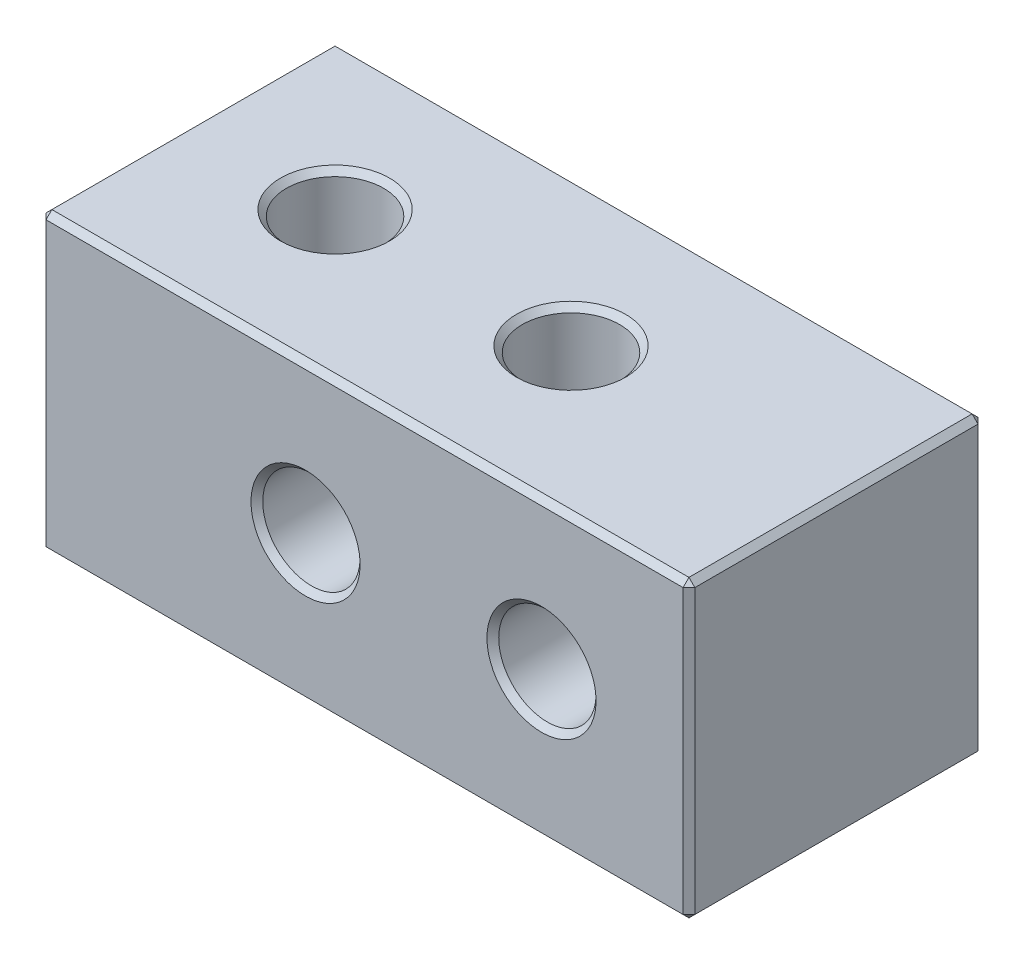
SolidWorks part; units mm, degrees
ref_plane "前视基准面" through (0, 0, 0) normal (0, 0, 1) x (1, 0, 0)
ref_plane "上视基准面" through (0, 0, 0) normal (0, 1, 0) x (1, 0, 0)
ref_plane "右视基准面" through (0, 0, 0) normal (1, 0, 0) x (0, 0, -1)
sketch "草图1" plane through (0, 0, 0) normal (0, 1, 0) x (1, 0, 0)
  line L1 (-11, 5) -> (11, 5)
  line L2 (-11, 5) -> (-11, -5)
  line L3 (-11, -5) -> (11, -5)
  line L4 (11, 5) -> (11, -5)
  line L5 (-11, 5) -> (11, -5) construction
  line L6 (-11, -5) -> (11, 5) construction
  point P0 (0, 0)
  dimension "D1" = 10
  dimension "D2" = 22
extrude "凸台-拉伸1" add sketch "草图1" along normal mid plane 10
hole_wizard "M4 螺纹孔1" positions "草图4" profile "草图6" tap size "M4" standard "GB" end condition through all
sketch "草图4" plane through (0, 5, 0) normal (0, 1, 0) x (1, 0, 0)
  line L0 (-11, 5) -> (-11, -5) construction
  line L1 (0, 0) -> (-50000, 0) construction
  point P0 (-6, 0)
  point P2 (2, 0)
  dimension "D1" = 5
  dimension "D2" = 8
sketch "草图6" plane through (-6, 5, 0) normal (1, 0, 0) x (0, 0, 1)
  line L0 (0, 0) -> (0, 10)
  line L1 (0, 10) -> (1.65, 10)
  line L2 (1.65, 10) -> (1.65, 0)
  line L5 (1.65, 0) -> (0, 0)
  line L11 (0, -6.35) -> (0, 107.95) construction
  dimension "通孔螺纹孔钻头直径" = 3.3
  dimension "通孔螺纹孔钻头深度" = 10
cosmetic thread "孔螺蚊线1" parameters "D2"=4
cosmetic thread "孔螺蚊线5" parameters "D2"=4
hole_wizard "M4 螺纹孔2" positions "草图7" profile "草图8" tap size "M4" standard "GB" end condition through all
sketch "草图7" plane through (0, 0, -5) normal (0, 0, -1) x (-1, 0, 0)
  line L0 (0, 0) -> (-50000, 0) construction
  line L1 (-11, 5) -> (-11, -5) construction
  point P0 (-6, 0)
  point P2 (2, 0)
  dimension "D1" = 5
  dimension "D2" = 8
sketch "草图8" plane through (6, 0, -5) normal (1, 0, 0) x (0, 1, 0)
  line L0 (0, 0) -> (0, 10)
  line L1 (0, 10) -> (1.65, 10)
  line L2 (1.65, 10) -> (1.65, 0)
  line L5 (1.65, 0) -> (0, 0)
  line L11 (0, -6.35) -> (0, 107.95) construction
  dimension "通孔螺纹孔钻头直径" = 3.3
  dimension "通孔螺纹孔钻头深度" = 10
cosmetic thread "孔螺蚊线3" parameters "D2"=4
cosmetic thread "孔螺蚊线4" parameters "D2"=4
chamfer "倒角1" distance 0.2 angle 45 20 edges at (2, -5, 1.65) (-6, -5, 1.65) (-3.65, 0, 5) (4.35, 0, 5) (2, 5, 1.65) (-6, 5, 1.65) (-11, -5, 0) (11, -5, 0) (-11, 0, 5) (0, -5, 5) (11, 0, 5) (0, 5, 5) (-11, 5, 0) (11, 5, 0) (11, 0, -5) (0, 5, -5) (-11, 0, -5) (0, -5, -5) (-3.65, 0, -5) (4.35, 0, -5)
